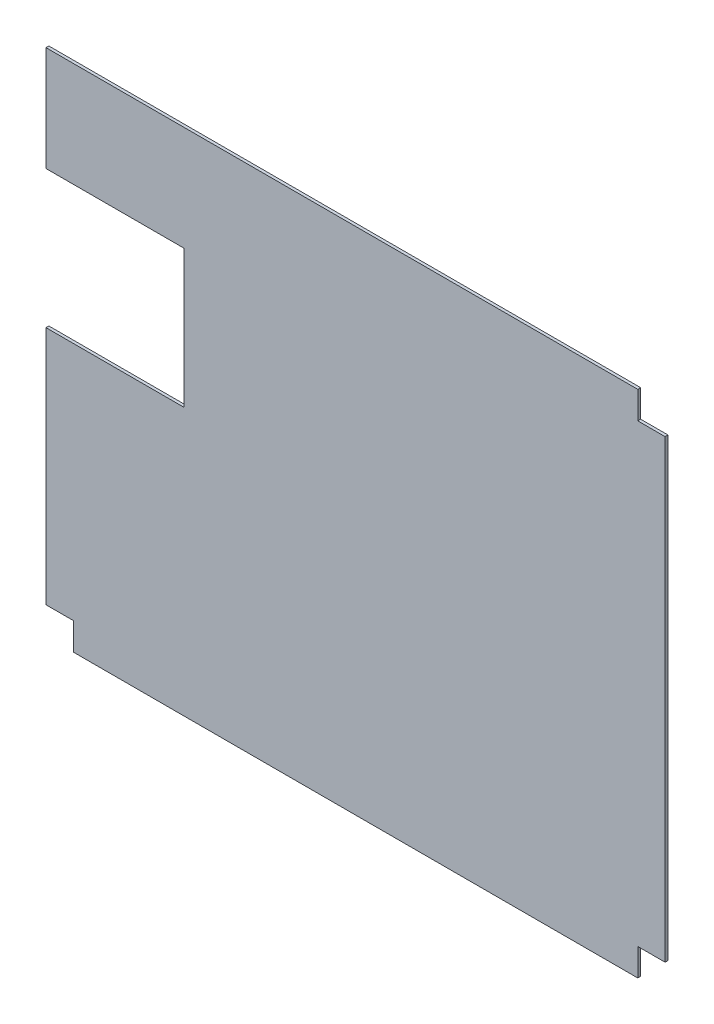
SolidWorks part; units mm, degrees
ref_plane "Alzado" through (0, 0, 0) normal (0, 0, 1) x (1, 0, 0)
ref_plane "Planta" through (0, 0, 0) normal (0, 1, 0) x (1, 0, 0)
ref_plane "Vista lateral" through (0, 0, 0) normal (1, 0, 0) x (0, 0, -1)
sketch "Croquis1" plane through (0, 0, 0) normal (0, 0, 1) x (1, 0, 0)
  line L0 (-205.7704, 310.6) -> (-205.7704, -74.4)
  line L1 (-205.7704, -74.4) -> (-175.7704, -74.4)
  line L2 (-175.7704, -74.4) -> (-175.7704, -104.4)
  line L3 (-175.7704, -104.4) -> (444.2296, -104.4)
  line L4 (444.2296, -104.4) -> (444.2296, -74.4)
  line L5 (444.2296, -74.4) -> (474.2296, -74.4)
  line L6 (474.2296, -74.4) -> (474.2296, 425.6)
  line L7 (474.2296, 425.6) -> (444.2296, 425.6)
  line L8 (444.2296, 425.6) -> (444.2296, 455.6)
  line L10 (-175.7704, 340.6) -> (-175.7704, 310.6)
  line L11 (-175.7704, 310.6) -> (-205.7704, 310.6)
  line L12 (-175.7704, 340.6) -> (-205.7704, 340.6)
  line L13 (-205.7704, 340.6) -> (-205.7704, 455.6)
  line L18 (444.2296, 455.6) -> (-205.7704, 455.6)
  dimension "D1" = 30
  dimension "D2" = 30
  dimension "D3" = 30
  dimension "D4" = 30
  dimension "D5" = 30
  dimension "D6" = 30
  dimension "D7" = 30
  dimension "D8" = 30
  dimension "D9" = 620
  dimension "D10" = 385
  dimension "D11" = 500
  dimension "D12" = 115
extrude "Saliente-Extruir1" add sketch "Croquis1" along normal blind 3.175
sketch "Croquis2" plane through (0, 0, 3.175) normal (0, 0, 1) x (1, 0, 0)
  line L0 (-205.7704, 304.25) -> (-169.4204, 304.25) construction
  line L1 (-205.7704, 310.6) -> (-205.7704, -74.4) construction
  line L2 (-169.4204, 304.25) -> (-169.4204, 219.25) construction
  line L7 (-169.4204, 219.25) -> (-84.4204, 219.25) construction
  line L8 (-84.4204, 219.25) -> (-84.4204, 304.25) construction
  line L9 (-84.4204, 304.25) -> (-169.4204, 304.25) construction
  line L10 (-169.4204, 304.25) -> (-131.8701, 266.6997) construction
  line L11 (-169.4204, 298.25) -> (-161.9204, 298.25) construction
  line L12 (-169.4204, 225.25) -> (-161.9204, 225.25) construction
  line L13 (-126.9204, 261.75) -> (-126.9204, 219.25) construction
  line L14 (-205.7704, 310.6) -> (-175.7704, 310.6)
  line L15 (-175.7704, 310.6) -> (-175.7704, 340.6)
  line L16 (-175.7704, 340.6) -> (-54.4204, 340.6)
  line L17 (-54.4204, 340.6) -> (-54.4204, 189.25)
  line L18 (-54.4204, 189.25) -> (-205.7704, 189.25)
  line L19 (-205.7704, 310.6) -> (-205.7704, -74.4) construction
  line L20 (-205.7704, 189.25) -> (-205.7704, 310.6)
  line L21 (-126.9204, 261.75) -> (-84.4204, 219.25) construction
  dimension "D9" = 30
  dimension "D10" = 30
  dimension "D1" = 6.35
  dimension "D2" = 6.35
  dimension "D3" = 85
  dimension "D4" = 85
  dimension "D5" = 6
  dimension "D6" = 7.5
  dimension "D7" = 6
  dimension "D8" = 7.5
extrude "Cortar-Extruir1" cut sketch "Croquis2" against normal blind 10
